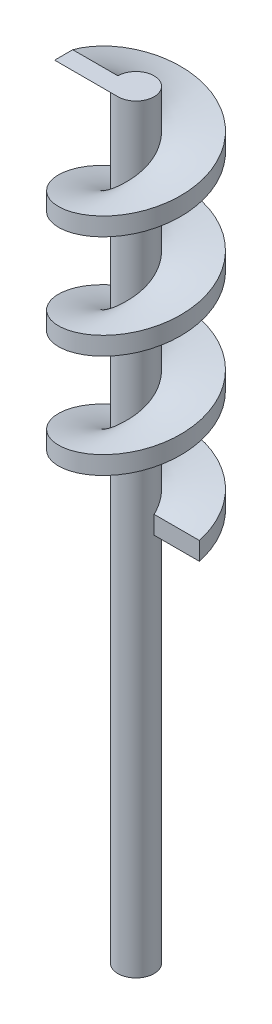
SolidWorks part; units mm, degrees
ref_plane "Front Plane" through (0, 0, 0) normal (0, 0, 1) x (1, 0, 0)
ref_plane "Top Plane" through (0, 0, 0) normal (0, 1, 0) x (1, 0, 0)
ref_plane "Right Plane" through (0, 0, 0) normal (1, 0, 0) x (0, 0, -1)
sketch "Sketch2" plane through (0, 0, 0) normal (0, 1, 0) x (1, 0, 0)
  circle A0 centre (0, 0) radius 1
  dimension "D1" = 2
extrude "Boss-Extrude1" add sketch "Sketch2" along normal blind 44
sketch "Sketch3" plane through (0, 44, 0) normal (0, 1, 0) x (1, 0, 0)
  circle A0 centre (0, 0) radius 3.5
  dimension "D1" = 7
curve "Helix/Spiral1" pitch 5.7143 height 20 turns 3.5
sketch "Sketch5" plane through (0, 0, 0) normal (0, 0, 1) x (1, 0, 0)
  line L0 (-1, 44) -> (-1, 0) construction
  line L1 (-3.4994, 44) -> (-1, 44)
  line L2 (-3.4994, 44) -> (-3.4994, 43)
  line L3 (-3.4994, 43) -> (-1, 43)
  line L4 (-1, 44) -> (-1, 43)
  line L5 (1, 44) -> (-1, 44) construction
  dimension "D1" = 1
  dimension "D2" = 2.4994
sweep "Sweep1" add profiles "Sketch5" path "Helix/Spiral1"
ref_plane "Plane1" through (-3.4994, 0, 0) normal (-1, 0, 0) x (0, -1, 0)
sketch "Sketch6" plane through (-3.4994, 0, 0) normal (-1, 0, 0) x (0, -1, 0)
  line L0 (-43, 0) -> (-44, 0)
  line L1 (-44, 0) -> (-43, 0) construction
  line L2 (-44, 0) -> (-44, 1)
  line L3 (-44, 1) -> (-44, -1) construction
  line L4 (-44, 1) -> (-43, 0)
  spline S0 degree 2 poles (-43, 0) (-42.7959, -0.7987) (-42.5918, -1.5184) (-42.3878, -2.238) (-42.1837, -2.736) (-41.9796, -3.234) (-41.7755, -3.4117) (-41.5714, -3.5894) (-41.3673, -3.4117) (-41.1633, -3.234) (-40.9592, -2.736) (-40.7551, -2.238) (-40.551, -1.5184) (-40.3469, -0.7987) (-40.1429, 0) (-39.9388, 0.7987) (-39.7347, 1.5184) (-39.5306, 2.238) (-39.3265, 2.736) (-39.1224, 3.234) (-38.9184, 3.4117) (-38.7143, 3.5894) (-38.5102, 3.4117) (-38.3061, 3.234) (-38.102, 2.736) (-37.898, 2.238) (-37.6939, 1.5184) (-37.4898, 0.7987) (-37.2857, 0) (-37.0816, -0.7987) (-36.8776, -1.5184) (-36.6735, -2.238) (-36.4694, -2.736) (-36.2653, -3.234) (-36.0612, -3.4117) (-35.8571, -3.5894) (-35.6531, -3.4117) (-35.449, -3.234) (-35.2449, -2.736) (-35.0408, -2.238) (-34.8367, -1.5184) (-34.6327, -0.7987) (-34.4286, 0) (-34.2245, 0.7987) (-34.0204, 1.5184) (-33.8163, 2.238) (-33.6122, 2.736) (-33.4082, 3.234) (-33.2041, 3.4117) (-33, 3.5894) (-32.7959, 3.4117) (-32.5918, 3.234) (-32.3878, 2.736) (-32.1837, 2.238) (-31.9796, 1.5184) (-31.7755, 0.7987) (-31.5714, 0) (-31.3673, -0.7987) (-31.1633, -1.5184) (-30.9592, -2.238) (-30.7551, -2.736) (-30.551, -3.234) (-30.3469, -3.4117) (-30.1429, -3.5894) (-29.9388, -3.4117) (-29.7347, -3.234) (-29.5306, -2.736) (-29.3265, -2.238) (-29.1224, -1.5184) (-28.9184, -0.7987) (-28.7143, 0) (-28.5102, 0.7987) (-28.3061, 1.5184) (-28.102, 2.238) (-27.898, 2.736) (-27.6939, 3.234) (-27.4898, 3.4117) (-27.2857, 3.5894) (-27.0816, 3.4117) (-26.8776, 3.234) (-26.6735, 2.736) (-26.4694, 2.238) (-26.2653, 1.5184) (-26.0612, 0.7987) (-25.8571, 0) (-25.6531, -0.7987) (-25.449, -1.5184) (-25.2449, -2.238) (-25.0408, -2.736) (-24.8367, -3.234) (-24.6327, -3.4117) (-24.4286, -3.5894) (-24.2245, -3.4117) (-24.0204, -3.234) (-23.8163, -2.736) (-23.6122, -2.238) (-23.4082, -1.5184) (-23.2041, -0.7987) (-23, 0) knots 0 0 0 0.017857 0.017857 0.035714 0.035714 0.053571 0.053571 0.071429 0.071429 0.089286 0.089286 0.107143 0.107143 0.125 0.125 0.142857 0.142857 0.160714 0.160714 0.178571 0.178571 0.196429 0.196429 0.214286 0.214286 0.232143 0.232143 0.25 0.25 0.267857 0.267857 0.285714 0.285714 0.303571 0.303571 0.321429 0.321429 0.339286 0.339286 0.357143 0.357143 0.375 0.375 0.392857 0.392857 0.410714 0.410714 0.428571 0.428571 0.446429 0.446429 0.464286 0.464286 0.482143 0.482143 0.5 0.5 0.517857 0.517857 0.535714 0.535714 0.553571 0.553571 0.571429 0.571429 0.589286 0.589286 0.607143 0.607143 0.625 0.625 0.642857 0.642857 0.660714 0.660714 0.678571 0.678571 0.696429 0.696429 0.714286 0.714286 0.732143 0.732143 0.75 0.75 0.767857 0.767857 0.785714 0.785714 0.803571 0.803571 0.821429 0.821429 0.839286 0.839286 0.857143 0.857143 0.875 0.875 0.875 weights 1 0.974928 1 0.974928 1 0.974928 1 0.974928 1 0.974928 1 0.974928 1 0.974928 1 0.974928 1 0.974928 1 0.974928 1 0.974928 1 0.974928 1 0.974928 1 0.974928 1 0.974928 1 0.974928 1 0.974928 1 0.974928 1 0.974928 1 0.974928 1 0.974928 1 0.974928 1 0.974928 1 0.974928 1 0.974928 1 0.974928 1 0.974928 1 0.974928 1 0.974928 1 0.974928 1 0.974928 1 0.974928 1 0.974928 1 0.974928 1 0.974928 1 0.974928 1 0.974928 1 0.974928 1 0.974928 1 0.974928 1 0.974928 1 0.974928 1 0.974928 1 0.974928 1 0.974928 1 0.974928 1 0.974928 1 0.974928 1 0.974928 1 construction
  dimension "D1" = 1
extrude "Boss-Extrude2" add sketch "Sketch6" against normal up to surface (3.4994 mm away) up to face at (0, 0, 1)
sketch "Sketch8" plane through (0, 0, 0) normal (0, -1, 0) x (1, 0, 0)
  circle A0 centre (0, 0) radius 1
  dimension "D1" = 2
extrude "Cut-Extrude1" cut sketch "Sketch8" against normal blind 2
